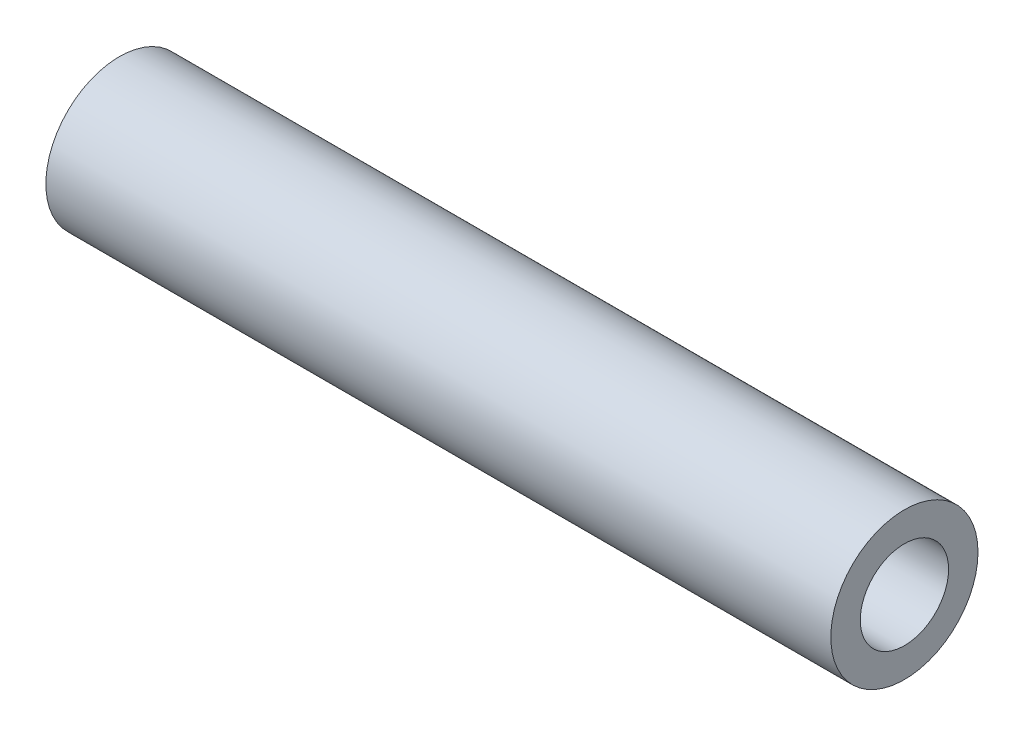
SolidWorks part; units mm, degrees
ref_plane "Front Plane" through (0, 0, 0) normal (0, 0, 1) x (1, 0, 0)
ref_plane "Top Plane" through (0, 0, 0) normal (0, 1, 0) x (1, 0, 0)
ref_plane "Right Plane" through (0, 0, 0) normal (1, 0, 0) x (0, 0, -1)
sketch "Sketch1" plane through (0, 0, 0) normal (1, 0, 0) x (0, 0, -1)
  circle A0 centre (0, 0) radius 2.286
  circle A1 centre (0, 0) radius 3.81
  dimension "D1" = 4.572
  dimension "D2" = 7.62
extrude "Boss-Extrude1" add sketch "Sketch1" along normal blind 40.64
